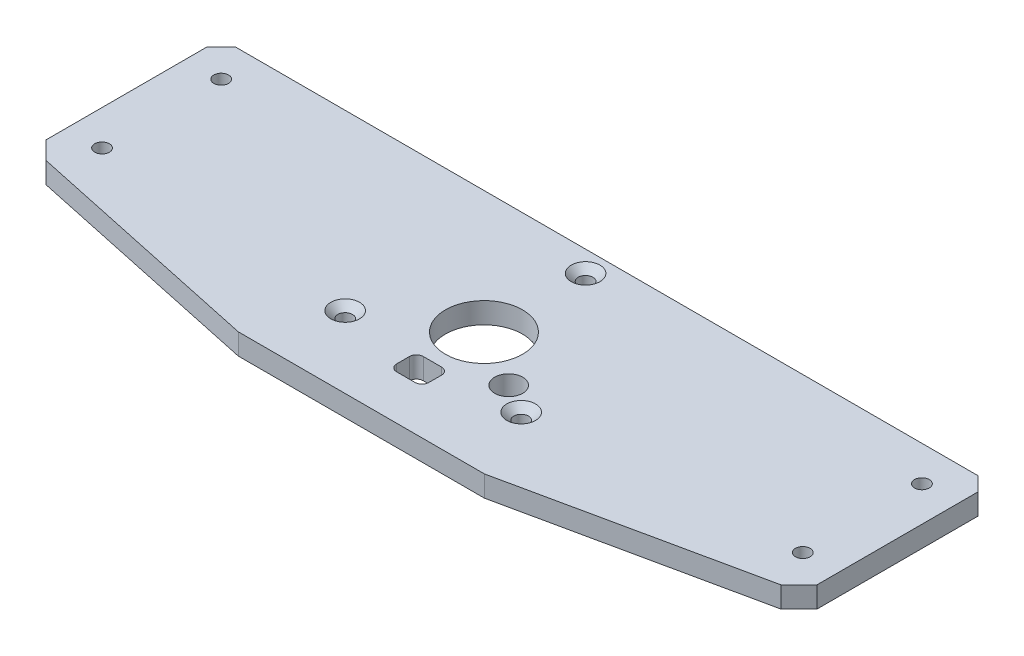
SolidWorks part; units mm, degrees
ref_plane "前视基准面" through (0, 0, 0) normal (0, 0, 1) x (1, 0, 0)
ref_plane "上视基准面" through (0, 0, 0) normal (0, 1, 0) x (1, 0, 0)
ref_plane "右视基准面" through (0, 0, 0) normal (1, 0, 0) x (0, 0, -1)
sketch "草图1" plane through (0, 0, 0) normal (0, 1, 0) x (1, 0, 0)
  line L1 (110, -35) -> (-110, -35)
  line L2 (110, -35) -> (110, 35)
  line L3 (110, 35) -> (-110, 35)
  line L4 (-110, -35) -> (-110, 35)
  line L5 (110, -35) -> (-110, 35) construction
  line L6 (110, 35) -> (-110, -35) construction
  line L7 (100, -25) -> (-100, -25) construction
  line L8 (100, -25) -> (100, 25) construction
  line L9 (100, 25) -> (-100, 25) construction
  line L10 (-100, -25) -> (-100, 25) construction
  line L11 (100, -25) -> (-100, 25) construction
  line L12 (100, 25) -> (-100, -25) construction
  circle A0 centre (-100, 25) radius 2.1
  circle A2 centre (100, 25) radius 2.1
  circle A4 centre (0, 0) radius 29 construction
  circle A5 centre (0, 29) radius 2.1
  circle A6 centre (25.1147, -14.5) radius 2.1
  circle A7 centre (-25.1147, -14.5) radius 2.1
  circle A8 centre (0, 0) radius 11
  circle A9 centre (-100, -9) radius 2.1
  circle A10 centre (100, -9) radius 2.1
  point P0 (0, 0)
  point P5 (0, 0)
  point P26 (0, 0)
  dimension "D3" = 4.2
  dimension "D4" = 58
  dimension "D5" = 4.2
  dimension "D9" = 22
  dimension "D10" = 34
  dimension "D1" = 200
  dimension "D2" = 10
  dimension "D7" = 70
  dimension "D8" = 10
  dimension "D6" = 3
extrude "凸台-拉伸1" add sketch "草图1" along normal mid plane 6
sketch "草图2" plane through (0, 3, 0) normal (0, 1, 0) x (1, 0, 0)
  line L0 (0, 0) -> (25.1147, -14.5) construction
  circle A0 centre (16.671, -9.625) radius 4
  dimension "D1" = 19.25
  dimension "D2" = 8
extrude "切除-拉伸1" cut sketch "草图2" against normal through all
sketch "草图3" plane through (0, 3, 0) normal (0, 1, 0) x (1, 0, 0)
  line L0 (4.6, -20.3) -> (4.6, -16.7)
  line L1 (3.1, -20.8) -> (-3.1, -20.8) construction
  line L2 (3.1, -20.8) -> (3.1, -16.2) construction
  line L3 (3.1, -16.2) -> (-3.1, -16.2) construction
  line L4 (-3.1, -20.8) -> (-3.1, -16.2) construction
  line L5 (3.1, -20.8) -> (-3.1, -16.2) construction
  line L6 (3.1, -16.2) -> (-3.1, -20.8) construction
  line L7 (2.6, -14.7) -> (-2.6, -14.7)
  line L8 (-4.6, -20.3) -> (-4.6, -16.7)
  line L9 (2.6, -22.3) -> (-2.6, -22.3)
  line L10 (-4.6, -22.3) -> (-4.6, -14.7) construction
  line L11 (4.6, -22.3) -> (-4.6, -22.3) construction
  line L12 (4.6, -22.3) -> (4.6, -14.7) construction
  line L13 (4.6, -14.7) -> (-4.6, -14.7) construction
  arc A0 (-4.6, -20.3) -> (-2.6, -22.3) centre (-2.6, -20.3) ccw
  arc A1 (4.6, -20.3) -> (2.6, -22.3) centre (2.6, -20.3) cw
  arc A2 (4.6, -16.7) -> (2.6, -14.7) centre (2.6, -16.7) ccw
  arc A3 (-2.6, -14.7) -> (-4.6, -16.7) centre (-2.6, -16.7) ccw
  point P0 (0, -18.5)
  dimension "D5" = 2
  dimension "D1" = 18.5
  dimension "D2" = 4.6
  dimension "D3" = 6.2
  dimension "D4" = 1.5
extrude "切除-拉伸2" cut sketch "草图3" against normal through all
chamfer "倒角1" distance 2 angle 45 3 edges at (25.1147, 3, 16.6) (-25.1147, 3, 16.6) (0, 3, -26.9)
sketch "草图5" plane through (0, 3, 0) normal (0, 1, 0) x (1, 0, 0)
  line L0 (-110, -19) -> (-35.1147, -35)
  line L1 (-110, 35) -> (-110, -35) construction
  line L2 (-110, -35) -> (110, -35) construction
  line L3 (-35.1147, -35) -> (-110, -35)
  line L4 (-110, -35) -> (-110, -19)
  line L5 (0, 0) -> (0, 35) construction
  line L6 (110, 35) -> (-110, 35) construction
  line L7 (35.1147, -35) -> (110, -35)
  line L8 (110, -19) -> (35.1147, -35)
  line L9 (110, -35) -> (110, -19)
  circle A0 centre (-25.1147, -14.5) radius 2.1 construction
  circle A1 centre (-100, -9) radius 2.1 construction
  dimension "D1" = 10
  dimension "D2" = 10
extrude "切除-拉伸3" cut sketch "草图5" against normal through all
chamfer "倒角3" distance 4 angle 45 4 edges at (110, 0, 19) (110, 0, -35) (-110, 0, -35) (-110, 0, 19)
